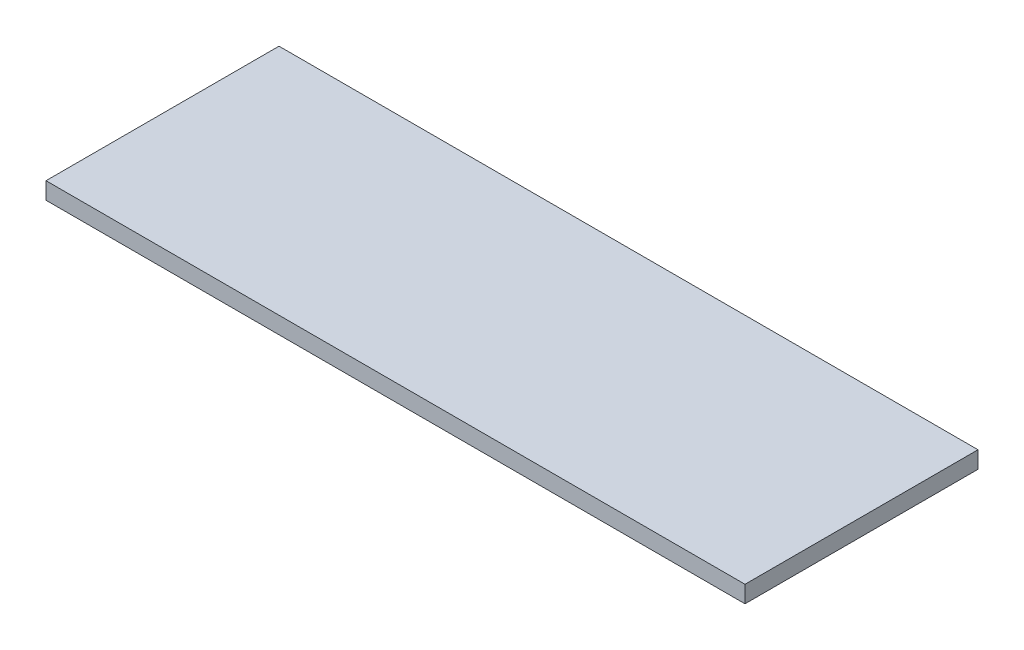
SolidWorks part; units mm, degrees
ref_plane "Alzado" through (0, 0, 0) normal (0, 0, 1) x (1, 0, 0)
ref_plane "Planta" through (0, 0, 0) normal (0, 1, 0) x (1, 0, 0)
ref_plane "Vista lateral" through (0, 0, 0) normal (1, 0, 0) x (0, 0, -1)
sketch "Croquis1" plane through (0, 0, 0) normal (0, 1, 0) x (1, 0, 0)
  line L1 (-33, -11) -> (33, -11)
  line L2 (-33, -11) -> (-33, 11)
  line L3 (-33, 11) -> (33, 11)
  line L4 (33, -11) -> (33, 11)
  line L5 (-33, -11) -> (33, 11) construction
  line L6 (-33, 11) -> (33, -11) construction
  point P0 (0, 0)
  dimension "D1" = 22
  dimension "D2" = 66
extrude "Saliente-Extruir1" add sketch "Croquis1" along normal blind 1.6
